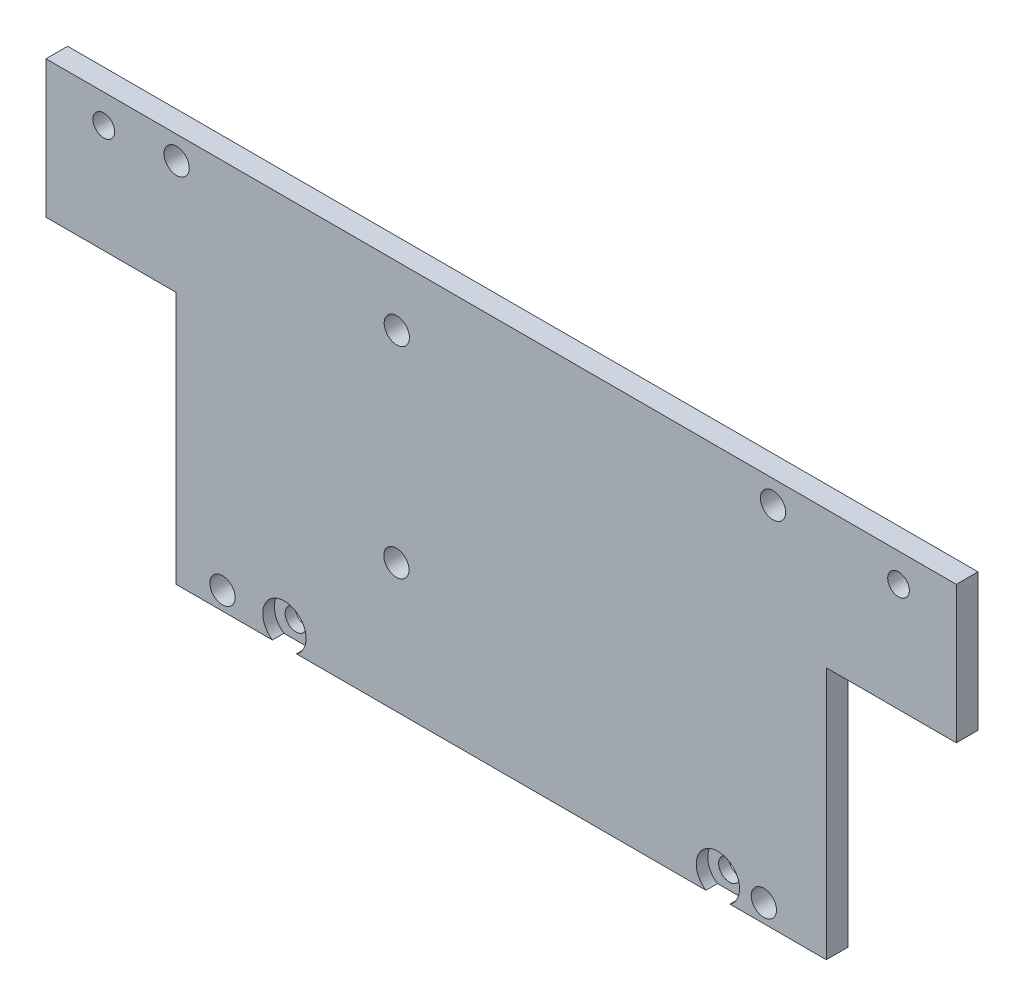
SolidWorks part; units mm, degrees
ref_plane "Front Plane" through (0, 0, 0) normal (0, 0, 1) x (1, 0, 0)
ref_plane "Top Plane" through (0, 0, 0) normal (0, 1, 0) x (1, 0, 0)
ref_plane "Right Plane" through (0, 0, 0) normal (1, 0, 0) x (0, 0, -1)
sketch "Sketch1" plane through (0, 0, 0) normal (0, 0, 1) x (1, 0, 0)
  line L1 (0, 0) -> (150, 0)
  line L2 (0, 0) -> (0, 54)
  line L3 (0, 54) -> (150, 54)
  line L4 (150, 0) -> (150, 54)
  dimension "D1" = 150
  dimension "D2" = 54
extrude "Boss-Extrude1" add sketch "Sketch1" along normal blind 3
sketch "Sketch2" plane through (0, 0, 0) normal (0, 0, -1) x (-1, 0, 0)
  line L0 (-75, 0) -> (-75, 54) construction
  line L1 (0, 0) -> (-150, 0) construction
  line L2 (-150, 54) -> (0, 54) construction
  line L3 (-30, 0) -> (-30, 35)
  line L8 (-150, 0) -> (-120, 0)
  line L9 (-150, 0) -> (-150, 35)
  line L10 (-150, 35) -> (-120, 35)
  line L11 (-120, 0) -> (-120, 35)
  line L12 (0, 35) -> (-30, 35)
  line L13 (0, 0) -> (0, 35)
  line L14 (0, 0) -> (-30, 0)
  dimension "D1" = 30
  dimension "D2" = 35
extrude "Cut-Extrude1" cut sketch "Sketch2" against normal through all
sketch "Sketch4" plane through (0, 0, 0) normal (0, 0, -1) x (-1, 0, 0)
  line L0 (-150, 54) -> (-138, 54)
  line L1 (-150, 54) -> (0, 54) construction
  line L2 (-138, 54) -> (-138, 35)
  line L3 (-120, 35) -> (-150, 35) construction
  line L4 (-138, 35) -> (-150, 35)
  line L5 (-150, 35) -> (-150, 54)
  line L6 (-75, 54) -> (-75, 0) construction
  line L7 (-30, 0) -> (-120, 0) construction
  line L8 (0, 35) -> (0, 54)
  line L9 (-12, 35) -> (0, 35)
  line L10 (-12, 54) -> (-12, 35)
  line L11 (0, 54) -> (-12, 54)
  dimension "D1" = 12
extrude "Cut-Extrude2" cut sketch "Sketch4" against normal blind 3
sketch "Sketch5" plane through (0, 0, 0) normal (0, 0, -1) x (-1, 0, 0)
  line L0 (-138, 54) -> (-12, 54) construction
  line L1 (-138, 35) -> (-138, 54) construction
  line L2 (-120, 0) -> (-120, 35) construction
  line L3 (-30, 0) -> (-120, 0) construction
  line L4 (-75, 54) -> (-75, 0) construction
  line L5 (-138, 54) -> (-12, 54) construction
  circle A0 centre (-130, 50) radius 1.5
  circle A1 centre (-105, 2.5) radius 1.5
  circle A2 centre (-45, 2.5) radius 1.5
  circle A3 centre (-20, 50) radius 1.5
  dimension "D1" = 3
  dimension "D2" = 4
  dimension "D3" = 8
  dimension "D4" = 15
  dimension "D5" = 2.5
extrude "Cut-Extrude3" cut sketch "Sketch5" against normal blind 3
sketch "Sketch7" plane through (0, 0, 3) normal (0, 0, 1) x (1, 0, 0)
  circle A0 centre (45, 2.5) radius 3
  circle A1 centre (105, 2.5) radius 3
  dimension "D1" = 3
  dimension "D2" = 3
extrude "Cut-Extrude5" cut sketch "Sketch7" against normal blind 1.6
sketch "Sketch8" plane through (0, 0, 3) normal (0, 0, 1) x (1, 0, 0)
  line L0 (138, 54) -> (12, 54) construction
  line L1 (12, 54) -> (12, 35) construction
  line L2 (138, 35) -> (138, 54) construction
  circle A0 centre (30.08, 50.8) radius 1.75
  circle A1 centre (60.56, 45.72) radius 1.75
  circle A2 centre (60.5, 17.84) radius 1.75
  circle A3 centre (36.43, 2.5) radius 1.75
  circle A4 centre (111.36, 2.5) radius 1.75
  circle A5 centre (112.63, 50.8) radius 1.75
  dimension "D1" = 3.5
  dimension "D2" = 3.2
  dimension "D3" = 18.08
  dimension "D4" = 8.28
  dimension "D5" = 48.56
  dimension "D6" = 48.5
  dimension "D7" = 36.16
  dimension "D9" = 51.5
  dimension "D10" = 25.37
  dimension "D12" = 51.5
  dimension "D13" = 26.64
  dimension "D8" = 24.43
  dimension "D11" = 3.2
extrude "Cut-Extrude6" cut sketch "Sketch8" against normal blind 3
